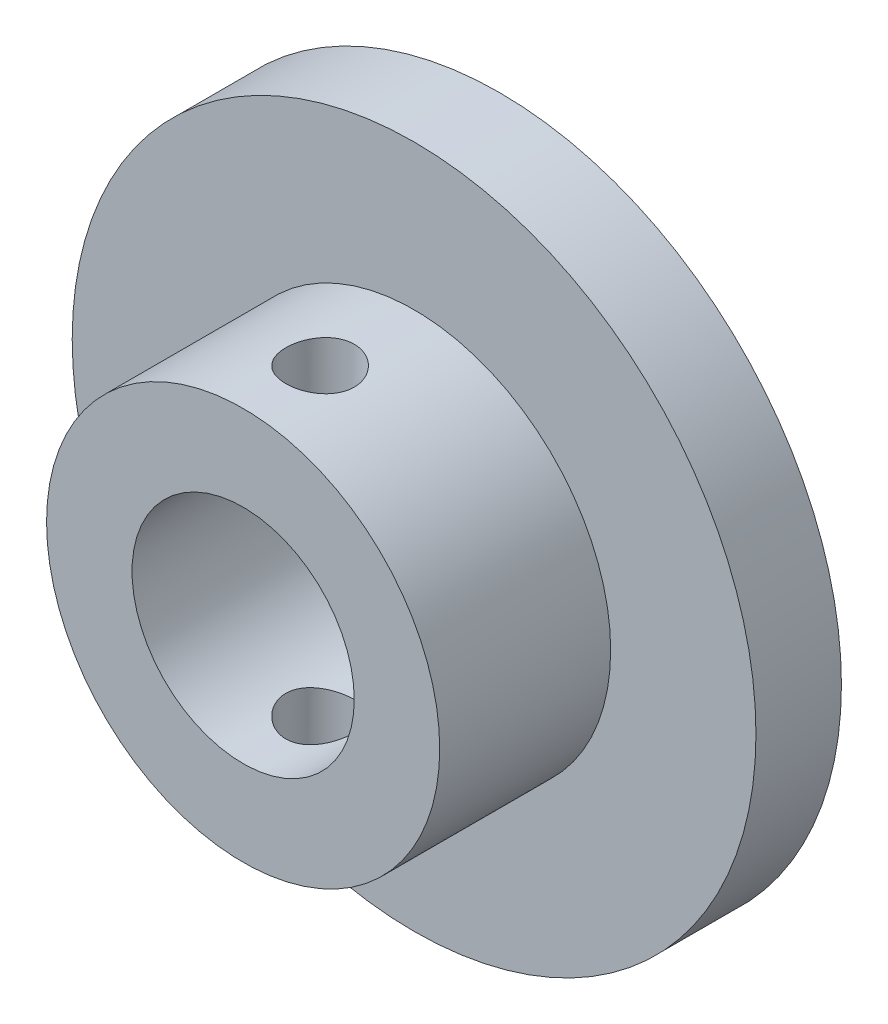
SolidWorks part; units mm, degrees
ref_plane "Alzado" through (0, 0, 0) normal (0, 0, 1) x (1, 0, 0)
ref_plane "Planta" through (0, 0, 0) normal (0, 1, 0) x (1, 0, 0)
ref_plane "Vista lateral" through (0, 0, 0) normal (1, 0, 0) x (0, 0, -1)
sketch "Croquis1" plane through (0, 0, 0) normal (0, 0, 1) x (1, 0, 0)
  circle A0 centre (0, 0) radius 20
  circle A1 centre (0, 0) radius 6.5
  dimension "D1" = 40
  dimension "D2" = 13
extrude "Saliente-Extruir1" add sketch "Croquis1" along normal mid plane 5
sketch "Croquis2" plane through (0, 0, 2.5) normal (0, 0, 1) x (1, 0, 0)
  circle A0 centre (0, 0) radius 6.5 construction
  circle A1 centre (0, 0) radius 6.5
  circle A2 centre (0, 0) radius 11.5
  dimension "D1" = 5
extrude "Saliente-Extruir2" add sketch "Croquis2" along normal blind 10
sketch "Croquis3" plane through (0, 0, 0) normal (0, 1, 0) x (1, 0, 0)
  line L0 (0, 0) -> (0, -8) construction
  circle A0 centre (0, -8) radius 2
  point P3 (0, -7.5859)
  dimension "D1" = 4
  dimension "D2" = 8
extrude "Cortar-Extruir1" cut sketch "Croquis3" against normal mid plane 30
